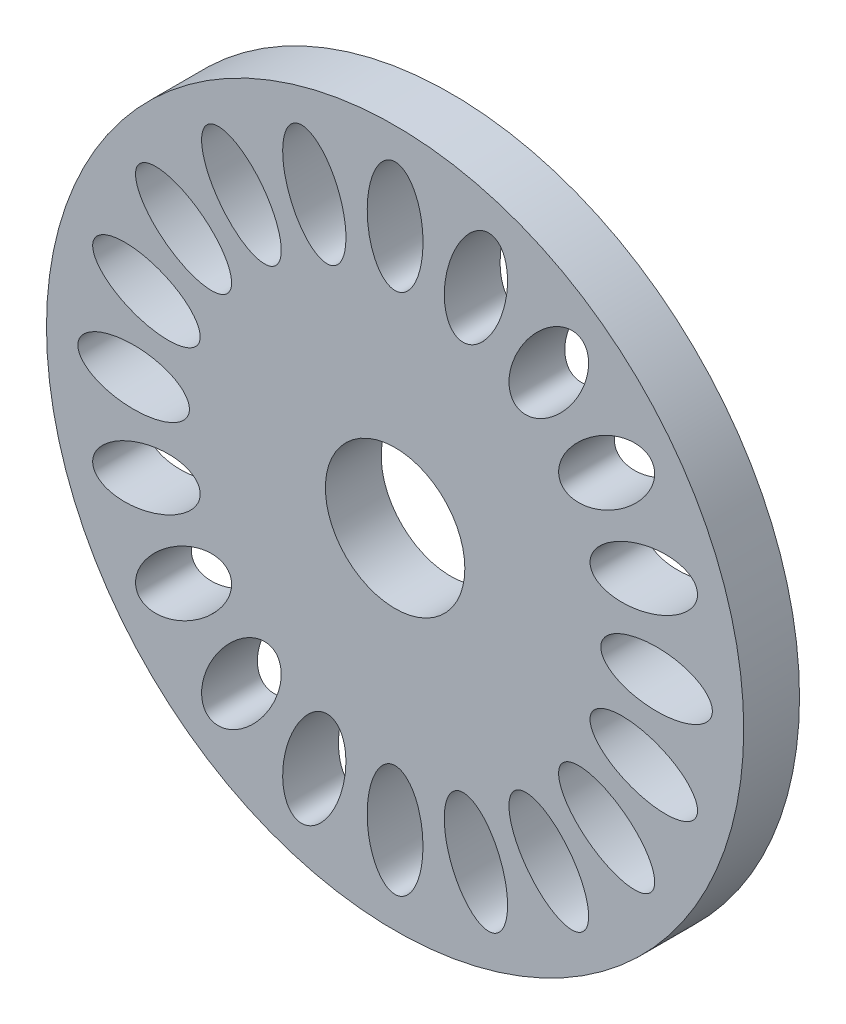
SolidWorks part; units mm, degrees
ref_plane "Front Plane" through (0, 0, 0) normal (0, 0, 1) x (1, 0, 0)
ref_plane "Top Plane" through (0, 0, 0) normal (0, 1, 0) x (1, 0, 0)
ref_plane "Right Plane" through (0, 0, 0) normal (1, 0, 0) x (0, 0, -1)
sketch "Sketch1" plane through (0, 0, 0) normal (0, 0, 1) x (1, 0, 0)
  line L0 (0, 0) -> (0, 12.5) construction
  line L1 (0, 12.5) -> (0, 6.25) construction
  line L2 (0, 6.25) -> (0, 9.375) construction
  circle A0 centre (0, 0) radius 12.5
  circle A1 centre (0, 0) radius 2.5
  ellipse E0 centre (0, 9.375) end of major axis (0, 7.375) minor radius 1
  ellipse E1 centre (2.897, 8.9162) end of major axis (3.5151, 10.8183) minor radius 1
  ellipse E2 centre (5.5105, 7.5845) end of major axis (6.6861, 9.2026) minor radius 1
  ellipse E3 centre (7.5845, 5.5105) end of major axis (5.9665, 4.3349) minor radius 1
  ellipse E4 centre (8.9162, 2.897) end of major axis (10.8183, 3.5151) minor radius 1
  ellipse E5 centre (9.375, 0) end of major axis (7.375, 0) minor radius 1
  ellipse E6 centre (8.9162, -2.897) end of major axis (10.8183, -3.5151) minor radius 1
  ellipse E7 centre (7.5845, -5.5105) end of major axis (9.2026, -6.6861) minor radius 1
  ellipse E8 centre (5.5105, -7.5845) end of major axis (4.3349, -5.9665) minor radius 1
  ellipse E9 centre (2.897, -8.9162) end of major axis (2.279, -7.014) minor radius 1
  ellipse E10 centre (0, -9.375) end of major axis (0, -7.375) minor radius 1
  ellipse E11 centre (-2.897, -8.9162) end of major axis (-2.279, -7.014) minor radius 1
  ellipse E12 centre (-5.5105, -7.5845) end of major axis (-4.3349, -5.9665) minor radius 1
  ellipse E13 centre (-7.5845, -5.5105) end of major axis (-9.2026, -6.6861) minor radius 1
  ellipse E14 centre (-8.9162, -2.897) end of major axis (-7.014, -2.279) minor radius 1
  ellipse E15 centre (-9.375, 0) end of major axis (-7.375, 0) minor radius 1
  ellipse E16 centre (-8.9162, 2.897) end of major axis (-10.8183, 3.5151) minor radius 1
  ellipse E17 centre (-7.5845, 5.5105) end of major axis (-5.9665, 4.3349) minor radius 1
  ellipse E18 centre (-5.5105, 7.5845) end of major axis (-4.3349, 5.9665) minor radius 1
  ellipse E19 centre (-2.897, 8.9162) end of major axis (-2.279, 7.014) minor radius 1
  dimension "D1" = 5
  dimension "D2" = 25
extrude "Boss-Extrude1" add sketch "Sketch1" along normal blind 2
